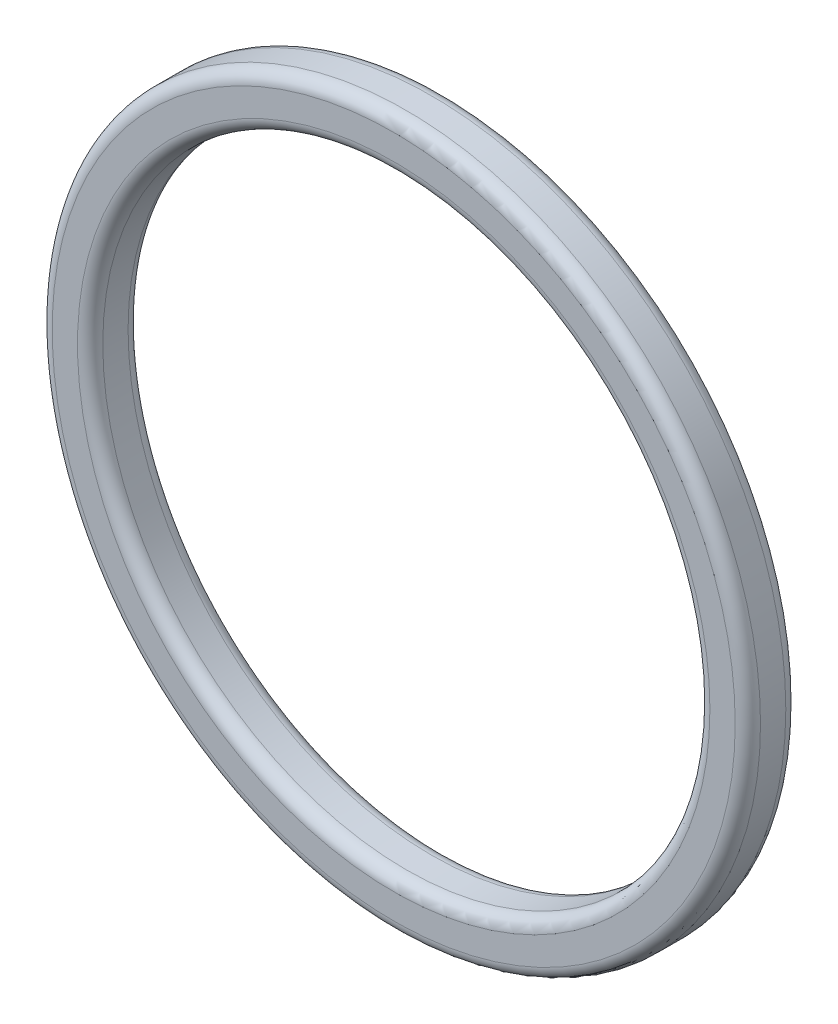
SolidWorks part; units mm, degrees
ref_plane "Front Plane" through (0, 0, 0) normal (0, 0, 1) x (1, 0, 0)
ref_plane "Top Plane" through (0, 0, 0) normal (0, 1, 0) x (1, 0, 0)
ref_plane "Right Plane" through (0, 0, 0) normal (1, 0, 0) x (0, 0, -1)
sketch "Sketch1" plane through (0, 0, 0) normal (0, 0, 1) x (1, 0, 0)
  circle A0 centre (0, 0) radius 6
  circle A1 centre (0, 0) radius 7
  dimension "D1" = 12
  dimension "D2" = 14
extrude "Boss-Extrude1" add sketch "Sketch1" along normal blind 1
fillet "Fillet1" radius 0.25 2 edges at (6, 0, 0) (7, 0, 0)
fillet "Fillet2" radius 0.25 2 edges at (6, 0, 1) (7, 0, 1)
